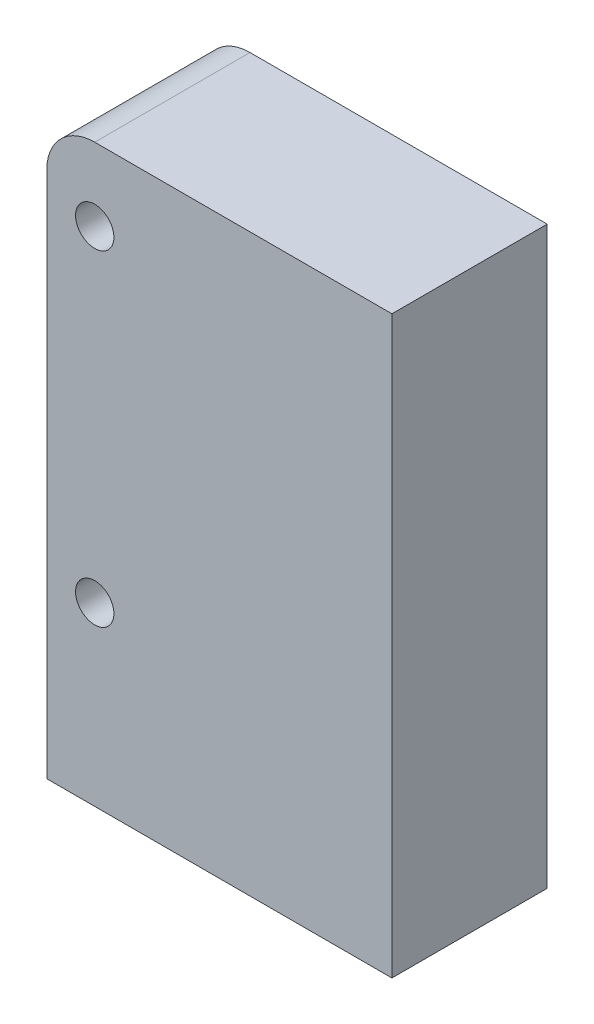
SolidWorks part; units mm, degrees
ref_plane "Plan de face" through (0, 0, 0) normal (0, 0, 1) x (1, 0, 0)
ref_plane "Plan de dessus" through (0, 0, 0) normal (0, 1, 0) x (1, 0, 0)
ref_plane "Plan de droite" through (0, 0, 0) normal (1, 0, 0) x (0, 0, -1)
sketch "Esquisse1" plane through (0, 0, 0) normal (0, 0, 1) x (1, 0, 0)
  line L1 (0, 0) -> (18, 0)
  line L2 (0, 0) -> (0, 30)
  line L3 (0, 30) -> (18, 30)
  line L4 (18, 0) -> (18, 30)
  dimension "D1" = 18
  dimension "D2" = 30
extrude "Boss.-Extru.1" add sketch "Esquisse1" along normal blind 8.1
sketch "Esquisse3" plane through (0, 0, 8.1) normal (0, 0, 1) x (1, 0, 0)
  line L0 (0, 30) -> (0, 0) construction
  line L3 (2.5, 9.2) -> (2.5, 26.2) construction
  line L4 (2.5, 26.2) -> (10.1767, 26.2) construction
  line L5 (0, 0) -> (18, 0) construction
  circle A2 centre (2.5, 26.2) radius 1
  circle A4 centre (2.5, 9.2) radius 1
  dimension "D1" = 2.5
  dimension "D5" = 17
  dimension "D3" = 2
  dimension "D2" = 9.2
extrude "Enlèv. mat.-Extru.1" cut sketch "Esquisse3" against normal through all
fillet "Congé1" radius 2.5 1 edges at (0, 30, 4.05)
